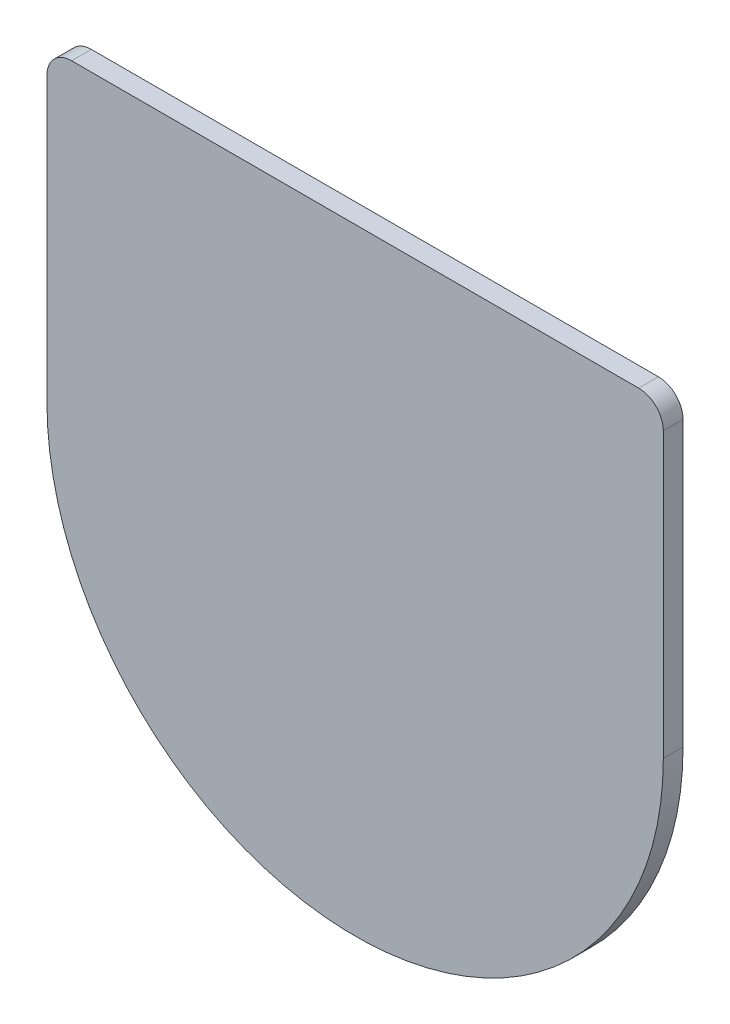
SolidWorks part; units mm, degrees
material "Pin"
ref_plane "Plan de face" through (0, 0, 0) normal (0, 0, 1) x (1, 0, 0)
ref_plane "Plan de dessus" through (0, 0, 0) normal (0, 1, 0) x (1, 0, 0)
ref_plane "Plan de droite" through (0, 0, 0) normal (1, 0, 0) x (0, 0, -1)
sketch "Esquisse1" plane through (0, 0, 0) normal (0, 0, 1) x (1, 0, 0)
  line L9 (-125, -62.5) -> (125, -62.5) construction
  line L10 (-125, -62.5) -> (-125, 52.5)
  line L11 (-115, 62.5) -> (115, 62.5)
  line L12 (125, -62.5) -> (125, 52.5)
  line L13 (-125, -62.5) -> (125, 62.5) construction
  line L14 (-125, 62.5) -> (125, -62.5) construction
  arc A8 (-125, -62.5) -> (125, -62.5) centre (0, -62.5) ccw
  arc A9 (115, 62.5) -> (125, 52.5) centre (115, 52.5) cw
  arc A10 (-125, 52.5) -> (-115, 62.5) centre (-115, 52.5) cw
  point P0 (0, 0)
  point P7 (0, 62.5)
  point P8 (0, -187.5)
  dimension "D1" = 250
  dimension "D3" = 10
  dimension "D2" = 250
extrude "Boss.-Extru.1" add sketch "Esquisse1" along normal blind 8
